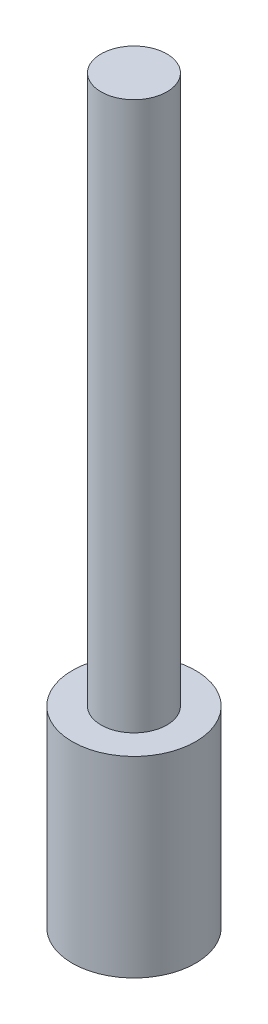
SolidWorks part; units mm, degrees
ref_plane "前视基准面" through (0, 0, 0) normal (0, 0, 1) x (1, 0, 0)
ref_plane "上视基准面" through (0, 0, 0) normal (0, 1, 0) x (1, 0, 0)
ref_plane "右视基准面" through (0, 0, 0) normal (1, 0, 0) x (0, 0, -1)
other "Configuration Table"
sketch "Sketch2" plane through (0, 0, 0) normal (0, 1, 0) x (1, 0, 0)
  circle A0 centre (0, 0) radius 4.5
extrude "Boss-Extrude1" add sketch "Sketch2" along normal blind 14
sketch "Sketch3" plane through (0, 14, 0) normal (0, 1, 0) x (1, 0, 0)
  circle A0 centre (0, 0) radius 2.4
sketch "Sketch4" plane through (0, 0, 0) normal (0, -1, 0) x (1, 0, 0)
  line L0 (-0.5967, 1.3762) -> (-1.3014, -0.7459)
  circle A0 centre (0, 0) radius 1.5
  dimension "D1" = 1
extrude "Cut-Extrude1" cut sketch "Sketch4" against normal blind 9 contours L0 A0
extrude "Boss-Extrude2" add sketch "Sketch3" along normal blind 40
